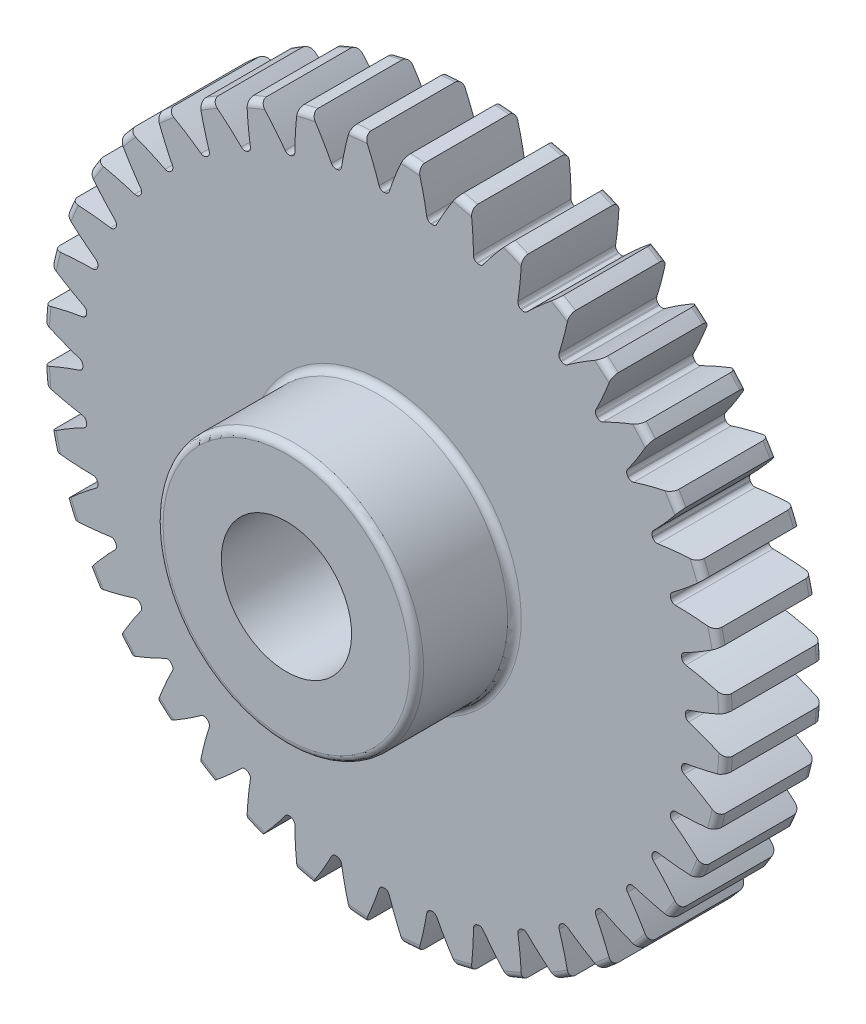
SolidWorks part; units mm, degrees
ref_plane "Front Plane" through (0, 0, 0) normal (0, 0, 1) x (1, 0, 0)
ref_plane "Top Plane" through (0, 0, 0) normal (0, 1, 0) x (1, 0, 0)
ref_plane "Right Plane" through (0, 0, 0) normal (1, 0, 0) x (0, 0, -1)
sketch "Sketch1" plane through (0, 0, 0) normal (0, 0, 1) x (1, 0, 0)
  line L0 (-508, 0) -> (508, 0) construction
  circle A0 centre (0, 0) radius 21 construction
  circle A1 centre (0, 0) radius 20 construction
  circle A2 centre (0, 0) radius 18.5 construction
  circle A3 centre (0, 0) radius 8 construction
  circle A4 centre (0, 0) radius 4 construction
  dimension "D2" = 1
  dimension "D3" = 2.5
  dimension "D1" = 2.5
sketch "Sketch2" plane through (0, 0, 0) normal (1, 0, 0) x (0, 0, -1)
  line L0 (0, 0) -> (-6, 0) construction
  line L1 (-6, 0) -> (-12, 0) construction
  dimension "Overall Width" = 12
  dimension "Face Width" = 6
sketch "Sketch4" plane through (0, 0, 0) normal (1, 0, 0) x (0, 0, -1)
  line L0 (-12, 4) -> (-12, 8)
  line L1 (-12, 8) -> (-6, 8)
  line L2 (-6, 8) -> (-6, 21)
  line L3 (-6, 21) -> (0, 21)
  line L4 (0, 21) -> (0, 4)
  line L5 (-6, 8) -> (-6, 0) construction
  line L6 (0, 21) -> (0, -21) construction
  line L7 (-6, 8) -> (0, 8) construction
  line L12 (-12, 4) -> (0, 4)
revolve "Revolve1" add sketch "Sketch4" angle 360 about L1
fillet "Fillet2" radius 0.42 4 edges at (0, 8, 12) (0, 8, 6) (0, 21, 6) (0, 21, 0)
sketch "Sketch7" plane through (0, 0, 6) normal (0, 0, 1) x (1, 0, 0)
  line L0 (0, 0) -> (0, 21) construction
  line L1 (0.7852, 19.9846) -> (1.1869, 20.9664) construction
  line L3 (1.6476, 20.9353) -> (1.5692, 19.9383) construction
  line L4 (1.5692, 19.9383) -> (1.4515, 18.443) construction
  line L5 (0, 0) -> (1.4515, 18.443) construction
  line L6 (0.7852, 19.9846) -> (0, 0) construction
  line L7 (0.7852, 19.9846) -> (0.8245, 20.9838) construction
  line L8 (0.7852, 19.9846) -> (0, 0) construction
  circle A0 centre (0, 0) radius 21 construction
  arc A1 (-0.027, 18.5) -> (0.027, 18.5) centre (0, 0) cw
  circle A2 centre (0, 0) radius 18.5 construction
  arc A3 (-0.7852, 19.9846) -> (0.7852, 19.9846) centre (0, 0) cw construction
  circle A4 centre (0, 0) radius 20 construction
  arc A5 (2.0774, 20.897) -> (1.2172, 20.9647) centre (0, 0) ccw construction
  arc A6 (0.7852, 19.9846) -> (2.3507, 19.8614) centre (0, 0) cw construction
  arc A7 (-1.2172, 20.9647) -> (1.2172, 20.9647) centre (0, 0) cw
  arc A8 (0.3122, 18.7056) -> (1.2172, 20.9647) centre (19.296, 12.4116) cw
  arc A9 (-0.3122, 18.7056) -> (-1.2172, 20.9647) centre (-19.296, 12.4116) ccw
  arc A10 (-0.027, 18.5) -> (-0.3122, 18.7056) centre (-0.0274, 18.8) cw
  arc A11 (0.027, 18.5) -> (0.3122, 18.7056) centre (0.0274, 18.8) ccw
  point P26 (-0.2447, 18.4984)
  point P29 (0.2447, 18.4984)
  dimension "D4" = 0.3
  dimension "D5" = 20
  dimension "D3" = 20
  dimension "D1" = 3.1416
  dimension "D2" = 1.5708
extrude "Cut-Extrude2" cut sketch "Sketch7" against normal through all
pattern_circular "CirPattern1" count 40 over 360 about axis through (0, 0, 0) along (0, 0, 1) of "Cut-Extrude2"
equation "\"D1@Sketch1\"=2.5*(\"Pitch Dia.@Sketch1\"/\"Number of Teeth@Sketch1\")"
equation "\"D1@CirPattern1\"=\"Number of Teeth@Sketch1\""
equation "\"D1@Fillet2\"=\"OD@Sketch1\"*.01"
equation "\"D1@Sketch7\"=3.14159*(\"Pitch Dia.@Sketch1\"/\"Number of Teeth@Sketch1\")"
equation "\"D2@Sketch7\"=\"D1@Sketch7\"/2"
equation "\"D4@Sketch7\"=\"D1@Sketch7\"*.0955"
equation "\"D5@Sketch7\"=\"Pitch Dia.@Sketch1\"/2"
